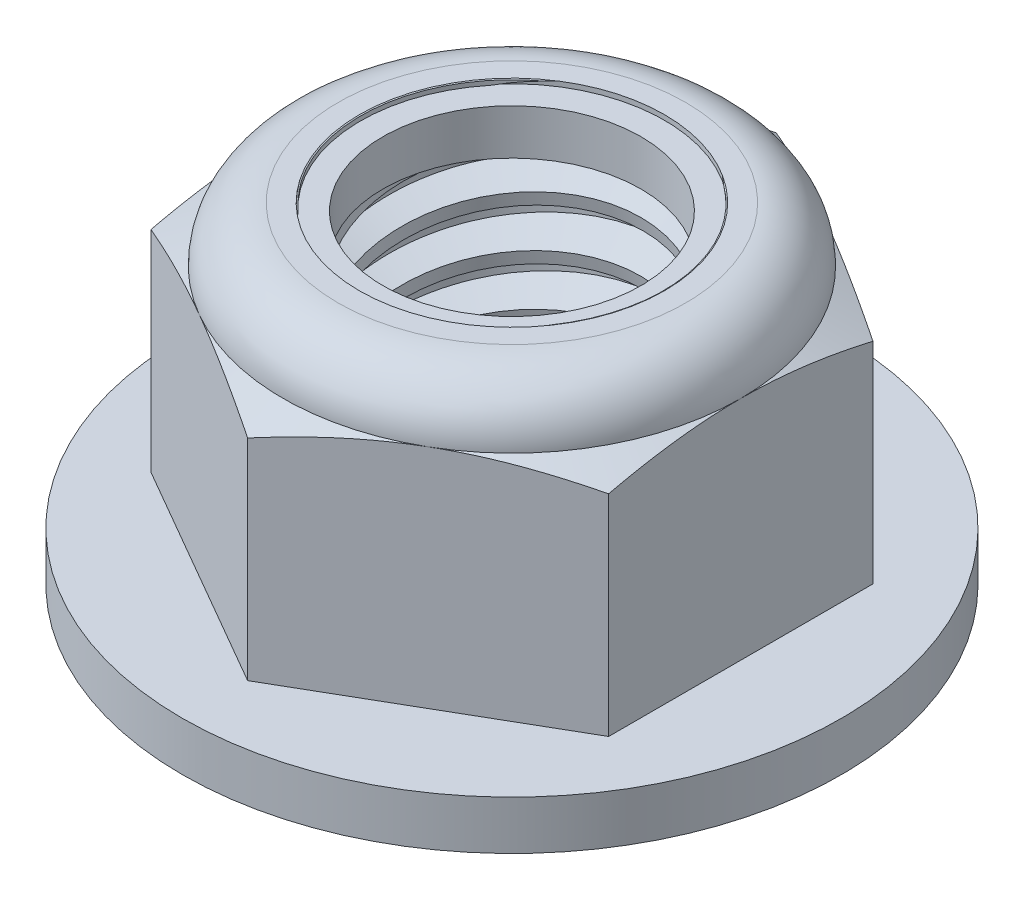
SolidWorks part; units mm, degrees
ref_plane "Front" through (0, 0, 0) normal (0, 0, 1) x (1, 0, 0)
ref_plane "Top" through (0, 0, 0) normal (0, 1, 0) x (1, 0, 0)
ref_plane "Right" through (0, 0, 0) normal (1, 0, 0) x (0, 0, -1)
sketch "Sketch1" plane through (0, 0, 0) normal (0, 1, 0) x (1, 0, 0)
  line L1 (0, 8.2489) -> (-7.1438, 4.1244)
  line L2 (-7.1438, 4.1244) -> (-7.1438, -4.1244)
  line L3 (-7.1438, -4.1244) -> (0, -8.2489)
  line L4 (0, -8.2489) -> (7.1437, -4.1244)
  line L5 (7.1437, -4.1244) -> (7.1437, 4.1244)
  line L6 (7.1437, 4.1244) -> (0, 8.2489)
  circle A0 centre (0, 0) radius 7.1438 construction
  dimension "Hex Flats" = 14.2875
extrude "Extrude1" add sketch "Sketch1" along normal blind 10.3187
sketch "Sketch8" plane through (0, 0, 0) normal (1, 0, 0) x (0, 0, -1)
  line L0 (0, 0) -> (10.287, 0)
  line L1 (10.287, 0) -> (10.287, 1.524)
  line L2 (10.287, 1.524) -> (0, 1.524)
  line L3 (0, 1.524) -> (0, 0)
  line L4 (0, 0) -> (0, -1.524) construction
  dimension "Flange Height" = 1.524
  dimension "Flange Dia" = 20.574
revolve "Revolve3" add sketch "Sketch8" angle 360 about L4
sketch "Sketch2" plane through (0, 0, 0) normal (1, 0, 0) x (0, 0, -1)
  line L0 (-4.7625, 0) -> (-4.7625, 10.3187) construction
  line L1 (0, 0) -> (4.7625, 0)
  line L2 (0, 0) -> (0, 10.3187)
  line L3 (0, 10.3187) -> (4.7625, 10.3187)
  line L4 (4.7625, 0) -> (4.7625, 10.3187)
  line L5 (-4.1244, 10.3187) -> (4.1244, 10.3187) construction
  line L7 (0, -4.7625) -> (0, 0) construction
  dimension "Thread Dia" = 9.525
revolve "Revolve1" add sketch "Sketch2" angle 360 about L7
sketch "Sketch3" plane through (0, 0, 0) normal (1, 0, 0) x (0, 0, -1)
  line L0 (4.7625, 10.3187) -> (-4.7625, 10.3187) construction
  line L1 (-4.7625, 10.3187) -> (-4.7625, 8.7312) construction
  line L2 (-4.7625, 8.7312) -> (4.7625, 10.3187) construction
  line L3 (4.7625, 10.3187) -> (4.7951, 10.123) construction
  line L4 (4.7951, 10.123) -> (5.0235, 8.7528)
  line L5 (5.0235, 8.7528) -> (4.0944, 9.1009)
  line L6 (4.0944, 9.1009) -> (4.0291, 9.4924)
  line L7 (4.0291, 9.4924) -> (4.7951, 10.123)
  line L8 (4.0617, 9.2967) -> (4.9093, 9.4379) construction
  line L9 (4.7625, 10.3187) -> (4.7625, 9.4135) construction
  line L10 (4.7625, 9.4135) -> (-4.7625, 7.826) construction
  line L11 (-4.7625, 7.826) -> (-4.7625, 8.7312) construction
  line L12 (-0.2832, 10.3187) -> (0.2832, 6.9207) construction
  line L13 (-4.7625, 0) -> (-4.7625, 10.3187) construction
  line L14 (0, 10.3187) -> (4.7625, 10.3187) construction
  line L15 (4.7625, 0) -> (4.7625, 10.3187) construction
  point P13 (0, 8.6197)
  dimension "D1" = 0.1984
  dimension "D2" = 0.3969
  dimension "Thread Pitch" = 1.5875
  dimension "D4" = 60
  dimension "D5" = 1.5875
revolve "Cut-Revolve1" cut sketch "Sketch3" angle 360 about L12
pattern_linear "LPattern1" count 7 spacing 1.5875 along (0, -1, 0) count 2 spacing 1.5875 along (0, 1, 0) of "Cut-Revolve1"
sketch "Sketch4" plane through (0, 0, 0) normal (1, 0, 0) x (0, 0, -1)
  line L0 (0, 10.3187) -> (4.7625, 10.3188)
  line L1 (4.7625, 10.3188) -> (4.0291, 9.9768)
  line L2 (4.0291, 9.9768) -> (4.0291, 0.342)
  line L3 (4.0291, 0.342) -> (4.7625, 0)
  line L4 (4.7625, 0) -> (0, 0)
  line L5 (0, 0) -> (0, 10.3187)
  line L6 (4.7625, 0) -> (4.7625, 10.3187) construction
  line L7 (0, 10.3187) -> (4.7625, 10.3187) construction
  line L8 (0, 0) -> (4.7625, 0) construction
  line L9 (0, 0) -> (0, 10.3187) construction
  line L10 (0, 10.3187) -> (0, 11.128) construction
  dimension "D1" = 25
revolve "Cut-Revolve2" cut sketch "Sketch4" angle 360 about L10
combine bodies "Combine1" operation type subtract main body 112 bodies to subtract 111
sketch "Sketch5" plane through (0, 0, 0) normal (1, 0, 0) x (0, 0, -1)
  line L0 (10.287, 1.524) -> (0, 1.524) construction
  line L1 (0, 0) -> (10.287, 0) construction
  line L2 (8.2489, 1.524) -> (8.2489, 8.0836)
  line L3 (8.2489, 8.0836) -> (7.1438, 8.599)
  line L4 (5.424, 10.3187) -> (5.424, 11.5887)
  line L5 (5.424, 11.5887) -> (9.5189, 11.5887)
  line L6 (9.5189, 11.5887) -> (9.5189, 1.524)
  line L9 (7.1438, 8.599) -> (7.1438, 0) construction
  line L13 (8.2489, 1.524) -> (9.5189, 1.524)
  line L15 (0, 0) -> (0, 11.5887) construction
  line L20 (0, 11.5887) -> (5.424, 11.5887) construction
  line L22 (0, 10.3187) -> (4.7625, 10.3187) construction
  arc A0 (7.1438, 8.599) -> (5.424, 10.3187) centre (5.424, 8.599) ccw
  dimension "D4" = 1.7198
  dimension "D1" = 1.27
  dimension "D2" = 115
  dimension "D3" = 10.3187
revolve "Cut-Revolve3" cut sketch "Sketch5" angle 360 about L15
sketch "Sketch6" plane through (0, 0, 0) normal (1, 0, 0) x (0, 0, -1)
  line L0 (0, 8.599) -> (6.9914, 8.599)
  line L1 (5.424, 10.1663) -> (4.7265, 10.1663)
  line L2 (0, 11.5887) -> (0, 8.599)
  line L3 (4.7265, 11.5887) -> (0, 11.5887)
  line L4 (0, 11.5887) -> (5.424, 11.5887) construction
  line L5 (0, 0) -> (0, 11.5887) construction
  line L6 (0, 11.5887) -> (0, 44.323) construction
  line L7 (4.7265, 10.1663) -> (4.7265, 11.5887)
  line L8 (5.424, 10.3187) -> (5.424, 10.1663) construction
  line L9 (4.7265, 10.1663) -> (4.0291, 10.1663) construction
  line L10 (4.0291, 10.1663) -> (4.0291, 9.9768) construction
  arc A0 (6.9914, 8.599) -> (5.424, 10.1663) centre (5.424, 8.599) ccw
  arc A1 (7.1438, 8.599) -> (5.424, 10.3187) centre (5.424, 8.599) ccw construction
  dimension "D1" = 0.1524
revolve "Cut-Revolve4" cut sketch "Sketch6" angle 360 about L6
sketch "Sketch7" plane through (0, 0, 0) normal (1, 0, 0) x (0, 0, -1)
  line L0 (4.0291, 8.6752) -> (6.9132, 8.6752)
  line L1 (5.424, 10.0901) -> (4.0291, 10.0901)
  line L2 (4.0291, 10.0901) -> (4.0291, 8.6752)
  line L3 (4.0291, 8.6752) -> (0, 8.6752) construction
  line L4 (0, 8.6752) -> (0, 10.0901) construction
  line L5 (0, 10.0901) -> (4.0291, 10.0901) construction
  line L6 (4.0291, 8.6752) -> (4.0291, 8.599) construction
  line L7 (0, 8.599) -> (6.9914, 8.599) construction
  line L8 (5.424, 10.0901) -> (5.424, 10.1663) construction
  arc A0 (6.9132, 8.6752) -> (5.424, 10.0901) centre (5.424, 8.599) ccw
  arc A2 (6.9914, 8.599) -> (5.424, 10.1663) centre (5.424, 8.599) ccw construction
  dimension "D1" = 0.0762
revolve "Revolve2" add sketch "Sketch7" angle 360 about L4
equation "\"D1@Sketch3\"=\"Thread Pitch@Sketch3\"/8"
equation "\"D2@Sketch3\"=\"Thread Pitch@Sketch3\"/4"
equation "\"D5@Sketch3\"=\"Thread Pitch@Sketch3\""
equation "\"D4@LPattern1\"=\"Thread Pitch@Sketch3\""
equation "\"D3@LPattern1\"=\"Thread Pitch@Sketch3\""
equation "\"D1@LPattern1\"=\"Height@Extrude1\"/\"Thread Pitch@Sketch3\""
equation "\"D4@Sketch5\"=\"Height@Extrude1\"/6"
